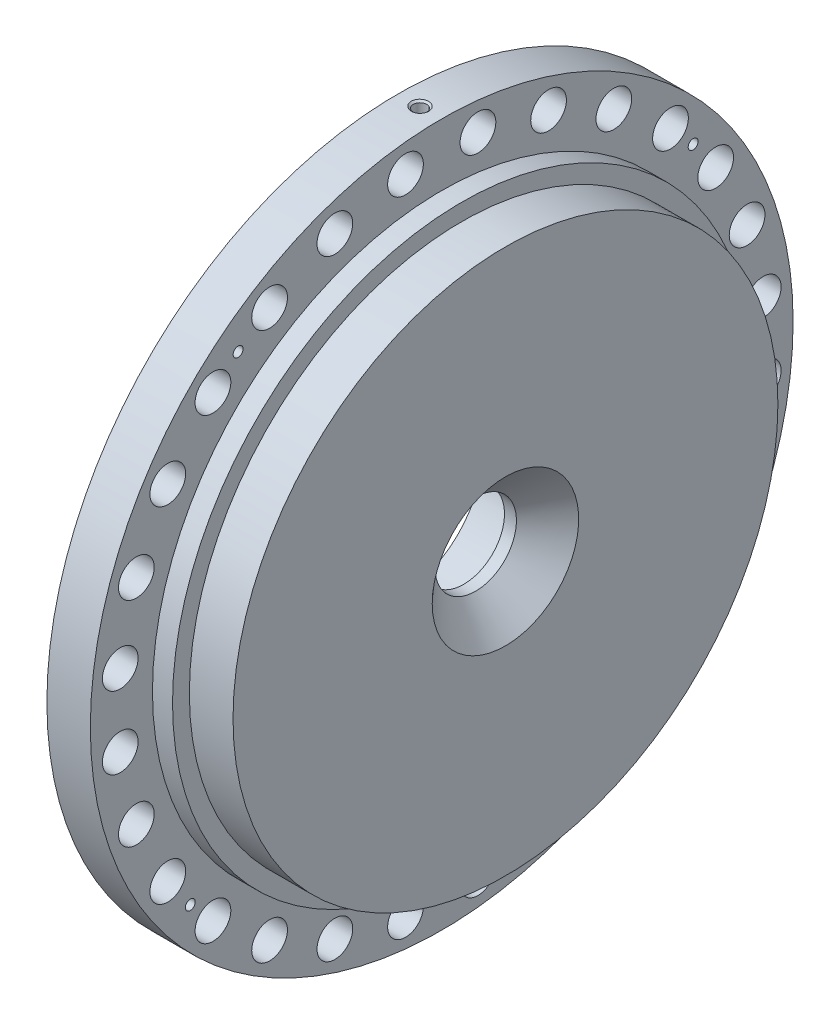
SolidWorks part; units mm, degrees
material "CD4Mc-U Duplex Stainless Steel"
ref_plane "Front Plane" through (0, 0, 0) normal (0, 0, 1) x (1, 0, 0)
ref_plane "Top Plane" through (0, 0, 0) normal (0, 1, 0) x (1, 0, 0)
ref_plane "Right Plane" through (0, 0, 0) normal (1, 0, 0) x (0, 0, -1)
sketch "Sketch1" plane through (0, 0, 0) normal (0, 0, 1) x (1, 0, 0)
  line L13 (-5.9944, 67.7545) -> (-5.9944, 180.9496)
  line L14 (-5.9944, 281.051) -> (28.7528, 281.051)
  line L15 (28.7528, 281.051) -> (28.7528, 231.3686)
  line L16 (28.7528, 231.3686) -> (44.8056, 231.3686)
  line L17 (44.8056, 231.3686) -> (44.8056, 217.9066)
  line L18 (44.8056, 217.9066) -> (79.7306, 217.9066)
  line L19 (79.7306, 217.9066) -> (79.7306, 58.5851)
  line L22 (0, 0) -> (159.4613, 0) construction
  line L27 (-5.9944, 228.9937) -> (0, 228.9937)
  line L28 (0, 228.9937) -> (0, 180.9496)
  line L29 (0, 180.9496) -> (-5.9944, 180.9496)
  line L30 (-5.9944, 228.9937) -> (-5.9944, 281.051)
  line L32 (-5.9944, 67.7545) -> (46.4058, 67.7545)
  line L35 (46.4058, 67.7545) -> (46.4058, 32.5628)
  line L36 (46.4058, 32.5628) -> (55.9308, 32.5628)
  line L37 (55.9308, 32.5628) -> (79.7306, 58.5851)
  dimension "D1" = 85.725
  dimension "D2" = 50.9778
  dimension "D3" = 50.8
  dimension "D4" = 9.525
  dimension "D5" = 281.051
  dimension "D6" = 228.9937
  dimension "D7" = 231.3686
  dimension "D8" = 217.9066
  dimension "D9" = 180.9496
  dimension "D11" = 5.9944
  dimension "D12" = 32.5628
  dimension "D13" = 52.4002
  dimension "D14" = 67.7545
  dimension "D16" = 58.5851
revolve "Revolve1" add sketch "Sketch1" angle 360 about L22
sketch "Sketch4" plane through (-5.9944, 0, 0) normal (-1, 0, 0) x (0, 0, 1)
  line L0 (0, 0) -> (0, 281.051) construction
  line L1 (0, 0) -> (28.9721, 257.1355) construction
  circle A1 centre (28.9721, 257.1355) radius 14.2875
  circle A2 centre (0, 0) radius 258.7625 construction
  dimension "D2" = 28.575
  dimension "D3" = 517.525
  dimension "D1" = 6.429
extrude "Cut-Extrude1" cut sketch "Sketch4" against normal through all
pattern_circular "CirPattern2" count 28 over 360 about axis through (0, 0, 0) along (1, 0, 0) of "Cut-Extrude1"
sketch "Sketch5" plane through (0, 0, 0) normal (-1, 0, 0) x (0, 0, 1)
  line L0 (0, 0) -> (53.4138, 199.3429) construction
  line L2 (0, 0) -> (0, 281.051) construction
  circle A0 centre (0, 0) radius 206.375 construction
  circle A1 centre (53.4138, 199.3429) radius 9.525
  circle A2 centre (0, 0) radius 281.051 construction
  dimension "D1" = 412.75
  dimension "D3" = 19.05
  dimension "D2" = 15
hole_wizard "3/4-10 Tapped Hole1" positions "Sketch7" profile "Sketch8" tap size "3/4-10" standard "ANSI Inch"
sketch "Sketch7" plane through (0, 0, 0) normal (-1, 0, 0) x (0, 0, 1)
  point P0 (53.4138, 199.3429)
sketch "Sketch8" plane through (0, 199.3429, 53.4138) normal (0, 1, 0) x (0, 0, 1)
  line L0 (0, 0) -> (0, 30.4074)
  line L1 (0, 30.4074) -> (8.3337, 25.4)
  line L2 (8.3337, 25.4) -> (8.3337, 1.8263)
  line L3 (8.3337, 1.8263) -> (10.16, 0)
  line L5 (10.16, 0) -> (0, 0)
  line L6 (-8.3337, 1.8263) -> (-10.16, 0) construction
  line L10 (0, 30.4074) -> (-8.3337, 25.4) construction
  line L11 (0, -6.35) -> (0, 107.95) construction
  dimension "Tap Drill Dia." = 16.6675
  dimension "Tap Drill Depth" = 25.4
  dimension "Near C'Sink Dia." = 20.32
  dimension "Near C'Sink Angle" = 90
  dimension "Drill Angle" = 118
cosmetic thread "Hole Thread2" parameters "D1"=12.7, "D2"=19.05
pattern_circular "CirPattern3" count 12 over 360 about axis through (0, 0, 0) along (1, 0, 0) of "3/4-10 Tapped Hole1"
cosmetic thread "Hole Thread3" parameters "D1"=12.7, "D2"=19.05
cosmetic thread "Hole Thread4" parameters "D1"=12.7, "D2"=19.05
cosmetic thread "Hole Thread5" parameters "D1"=12.7, "D2"=19.05
cosmetic thread "Hole Thread6" parameters "D1"=12.7, "D2"=19.05
cosmetic thread "Hole Thread7" parameters "D1"=12.7, "D2"=19.05
cosmetic thread "Hole Thread8" parameters "D1"=12.7, "D2"=19.05
cosmetic thread "Hole Thread9" parameters "D1"=12.7, "D2"=19.05
cosmetic thread "Hole Thread10" parameters "D1"=12.7, "D2"=19.05
cosmetic thread "Hole Thread11" parameters "D1"=12.7, "D2"=19.05
cosmetic thread "Hole Thread12" parameters "D1"=12.7, "D2"=19.05
cosmetic thread "Hole Thread13" parameters "D1"=12.7, "D2"=19.05
sketch "Sketch9" plane through (-5.9944, 0, 0) normal (-1, 0, 0) x (0, 0, 1)
  line L0 (0, 0) -> (0, 94.996) construction
  line L1 (0, 0) -> (67.1723, 67.1723) construction
  circle A0 centre (0, 0) radius 94.996 construction
  circle A1 centre (67.1723, 67.1723) radius 11.1125
  dimension "D1" = 189.992
  dimension "D3" = 22.225
  dimension "D2" = 45
hole_wizard "7/8-9 Tapped Hole1" positions "3DSketch1" profile "Sketch10" tap size "7/8-9" standard "ANSI Inch"
sketch3d "3DSketch1"
  point P0 (-5.9944, 67.1723, 67.1723)
sketch "Sketch10" plane through (-5.9944, 67.1723, 67.1723) normal (0, 1, 0) x (0, 0, 1)
  line L0 (0, 0) -> (0, 31.2422)
  line L1 (0, 31.2422) -> (9.7231, 25.4)
  line L2 (9.7231, 25.4) -> (9.7231, 2.0244)
  line L3 (9.7231, 2.0244) -> (11.7475, 0)
  line L5 (11.7475, 0) -> (0, 0)
  line L6 (-9.7231, 2.0244) -> (-11.7475, 0) construction
  line L10 (0, 31.2422) -> (-9.7231, 25.4) construction
  line L11 (0, -6.35) -> (0, 107.95) construction
  dimension "Tap Drill Dia." = 19.4462
  dimension "Tap Drill Depth" = 25.4
  dimension "Near C'Sink Dia." = 23.495
  dimension "Near C'Sink Angle" = 90
  dimension "Drill Angle" = 118
cosmetic thread "Hole Thread14" parameters "D1"=44.45, "D2"=22.225
pattern_circular "CirPattern4" count 4 over 360 about axis through (0, 0, 0) along (1, 0, 0) of "7/8-9 Tapped Hole1"
cosmetic thread "Hole Thread15" parameters "D1"=44.45, "D2"=22.225
cosmetic thread "Hole Thread16" parameters "D1"=44.45, "D2"=22.225
cosmetic thread "Hole Thread17" parameters "D1"=44.45, "D2"=22.225
sketch "Sketch11" plane through (-5.9944, 0, 0) normal (-1, 0, 0) x (0, 0, 1)
  line L0 (0, 0) -> (258.7625, 0) construction
  line L1 (0, 0) -> (201.0962, -162.8445) construction
  circle A0 centre (0, 0) radius 258.7625 construction
  circle A1 centre (201.0962, -162.8445) radius 4.7625
  dimension "D1" = 517.525
  dimension "D3" = 9.525
  dimension "D2" = 39
hole_wizard "Tap Drill for 3/8-16 Tap1" positions "3DSketch2" profile "Sketch12" hole size "3/8-16" standard "ANSI Inch"
sketch3d "3DSketch2"
  point P0 (-5.9944, -162.8445, 201.0962)
sketch "Sketch12" plane through (-5.9944, -162.8445, 201.0962) normal (0, 1, 0) x (0, 0, 1)
  line L0 (0, 0) -> (0, 43.0247)
  line L1 (0, 43.0247) -> (3.9687, 40.64)
  line L2 (3.9687, 40.64) -> (3.9687, 0.635)
  line L3 (3.9687, 0.635) -> (4.6037, 0)
  line L5 (4.6037, 0) -> (0, 0)
  line L6 (-3.9687, 0.635) -> (-4.6037, 0) construction
  line L10 (0, 43.0247) -> (-3.9688, 40.64) construction
  line L11 (0, -6.35) -> (0, 107.95) construction
  dimension "Hole Dia." = 7.9375
  dimension "Hole Depth" = 40.64
  dimension "Near C'Sink Dia." = 9.2075
  dimension "Near C'Sink Angle" = 90
  dimension "Drill Angle" = 118
pattern_circular "CirPattern5" count 4 over 360 about axis through (0, 0, 0) along (1, 0, 0) of "Tap Drill for 3/8-16 Tap1"
ref_plane "Plane2" through (0, 281.051, 0) normal (0, 1, 0) x (1, 0, 0)
sketch "Sketch20" plane through (0, 281.051, 0) normal (0, 1, 0) x (1, 0, 0)
  line L0 (-5.9944, 0) -> (11.3792, 0) construction
  line L1 (-5.9944, 281.051) -> (-5.9944, -281.051) construction
  dimension "D1" = 17.3736
hole_wizard "1/2-13 Tapped Hole4" positions "3DSketch8" profile "Sketch19" tap size "1/2-13" standard "ANSI Inch"
sketch3d "3DSketch8"
  point P0 (11.3792, 281.051, 0)
sketch "Sketch19" plane through (11.3792, 281.051, 0) normal (1, 0, 0) x (0, 0, 1)
  line L0 (0, 0) -> (0, 38.2715)
  line L1 (0, 38.2715) -> (5.3581, 35.052)
  line L2 (5.3581, 35.052) -> (5.3581, 1.3651)
  line L3 (5.3581, 1.3651) -> (6.985, 0)
  line L5 (6.985, 0) -> (0, 0)
  line L6 (-5.3581, 1.3651) -> (-6.985, 0) construction
  line L10 (0, 38.2715) -> (-5.3581, 35.052) construction
  line L11 (0, -6.35) -> (0, 107.95) construction
  dimension "Tap Drill Dia." = 10.7163
  dimension "Tap Drill Depth" = 35.052
  dimension "Near C'Sink Dia." = 13.97
  dimension "Near C'Sink Angle" = 100
  dimension "Drill Angle" = 118
cosmetic thread "Hole Thread24" parameters "D1"=25.4, "D2"=12.7
